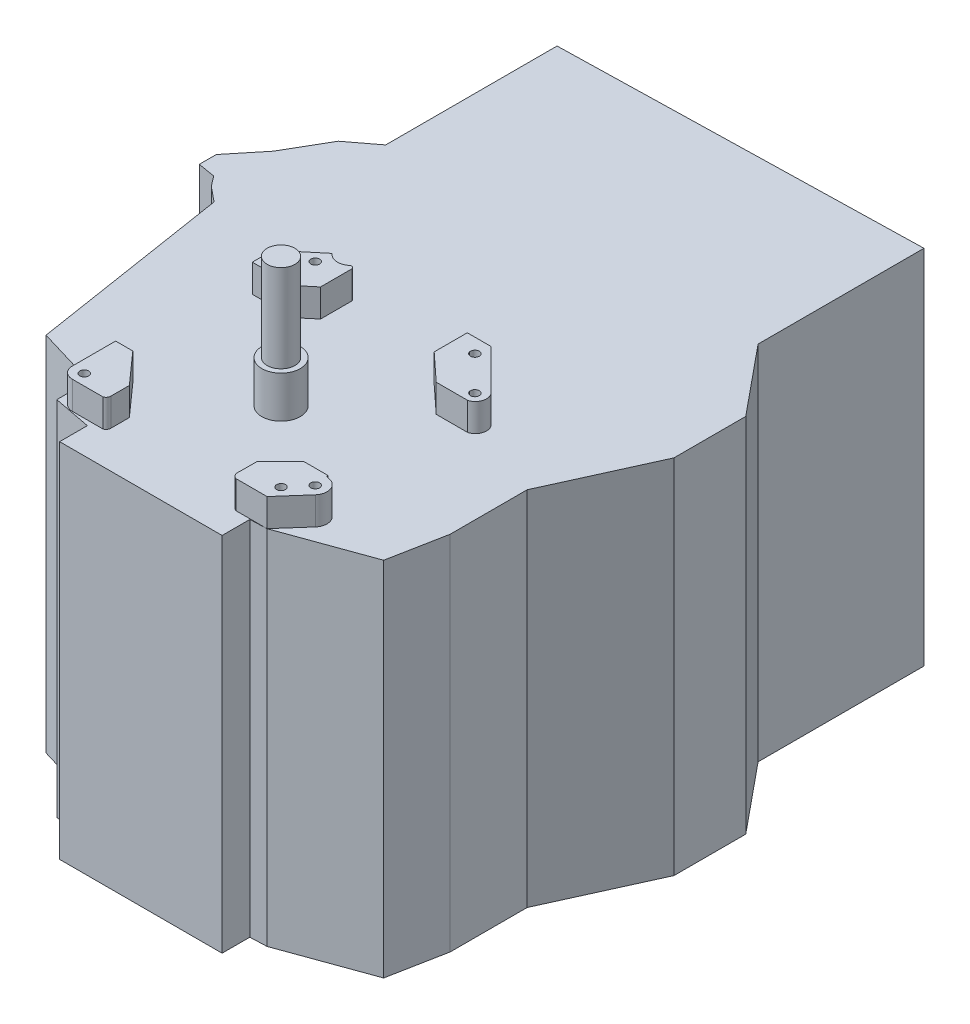
SolidWorks part; units mm, degrees
ref_plane "Front Plane" through (0, 0, 0) normal (0, 0, 1) x (1, 0, 0)
ref_plane "Top Plane" through (0, 0, 0) normal (0, 1, 0) x (1, 0, 0)
ref_plane "Right Plane" through (0, 0, 0) normal (1, 0, 0) x (0, 0, -1)
sketch "Sketch1" plane through (0, 0, 0) normal (0, 1, 0) x (1, 0, 0)
  line L0 (0.0612, 0.1182) -> (-126.9388, 0.1182) construction
  line L1 (-96.8371, 97.1503) -> (-71.6407, 118.188)
  line L2 (-50.3848, 114.8458) -> (-50.3848, 86.3868)
  line L3 (-50.3848, 86.3868) -> (-64.2052, 74.8474)
  line L4 (-64.2052, 74.8474) -> (-101.118, 74.8474)
  line L5 (-101.118, 74.8474) -> (-101.118, 86.3868)
  line L6 (74.669, 117.1527) -> (110.8217, 80.9999)
  line L7 (106.4734, 63.9008) -> (77.6795, 63.9008)
  line L8 (77.6795, 63.9008) -> (52.8172, 86.9128)
  line L9 (52.8172, 86.9128) -> (52.8172, 117.1527)
  line L10 (52.8172, 117.1527) -> (74.669, 117.1527)
  line L11 (101.9355, -59.2136) -> (79.8915, -59.2136)
  line L12 (79.8915, -59.2136) -> (58.6662, -80.129)
  line L13 (58.6662, -80.129) -> (58.5329, -98.2615)
  line L14 (62.5394, -103.6781) -> (90.8914, -103.6781)
  line L15 (90.8914, -103.6781) -> (111.5999, -80.2182)
  line L16 (-101.118, -49.8827) -> (-85.4463, -49.8827)
  line L17 (-85.4463, -49.8827) -> (-59.7593, -78.7019)
  line L18 (-59.7593, -78.7019) -> (-59.7593, -95.602)
  line L19 (-62.6519, -99.786) -> (-90.7515, -99.786)
  line L20 (-101.118, -90.5363) -> (-101.118, -49.8827)
  arc A0 (-71.6407, 118.188) -> (-54.1704, 116.6166) centre (-62.1198, 126.1375) ccw
  arc A1 (-54.1704, 116.6166) -> (-50.3848, 114.8458) centre (-52.6918, 114.8458) cw
  arc A2 (-101.118, 86.3868) -> (-96.8371, 97.1503) centre (-85.4463, 86.3868) cw
  arc A3 (110.8217, 80.9999) -> (106.4734, 63.9008) centre (103.5647, 73.7429) cw
  arc A4 (58.5329, -98.2615) -> (62.5394, -103.6781) centre (64.1419, -98.3027) ccw
  arc A5 (111.5999, -80.2182) -> (103.7376, -61.066) centre (102.9472, -72.5803) ccw
  arc A6 (103.7376, -61.066) -> (101.9355, -59.2136) centre (103.8701, -59.1342) cw
  arc A7 (-59.7593, -95.602) -> (-62.6519, -99.786) centre (-64.2316, -95.602) cw
  arc A8 (-90.7515, -99.786) -> (-101.118, -90.5363) centre (-90.7515, -89.3521) cw
  circle A9 centre (0, 0) radius 126.9678 construction
  dimension "D1" = 127
extrude "Boss-Extrude1" add sketch "Sketch1" along normal blind 25.4
sketch "Sketch2" plane through (0, 0, 0) normal (0, -1, 0) x (1, 0, 0)
  line L1 (-240.03, 129.54) -> (240.03, 129.54)
  line L2 (-240.03, 129.54) -> (-240.03, -429.26)
  line L3 (-240.03, -429.26) -> (240.03, -429.26)
  line L4 (240.03, 129.54) -> (240.03, -429.26)
  line L5 (-240.03, 129.54) -> (240.03, -429.26) construction
  line L6 (-240.03, -429.26) -> (240.03, 129.54) construction
  point P0 (0, -149.86)
  point P5 (0, 0)
  point P6 (0, 129.54)
  point P8 (-39.6101, -204.7195)
  dimension "D1" = 480.06
  dimension "D2" = 558.8
  dimension "D3" = 129.54
extrude "Boss-Extrude2" add sketch "Sketch2" along normal blind 330.2
sketch "Sketch3" plane through (0, 25.4, 0) normal (0, 1, 0) x (1, 0, 0)
  line L0 (-73.1456, 105.4562) -> (107.3629, -73.241) construction
  line L1 (0, -127) -> (0, 127) construction
  line L2 (127, 0) -> (-127, 0) construction
  line L3 (0, 0) -> (72.8442, 104.0323) construction
  line L4 (104.0323, 72.8442) -> (0, 0) construction
  line L5 (104.0323, -72.8442) -> (0, 0) construction
  line L6 (89.8026, -89.8026) -> (0, 0) construction
  line L7 (-89.8026, -89.8026) -> (0, 0) construction
  line L8 (-89.8026, 89.8026) -> (0, 0) construction
  line L9 (0, 0) -> (-72.8442, 104.0323) construction
  circle A0 centre (0, 0) radius 127 construction
  circle A1 centre (-72.8442, 104.0323) radius 4
  circle A2 centre (-89.8026, 89.8026) radius 4
  circle A3 centre (72.8442, 104.0323) radius 4
  circle A4 centre (104.0323, 72.8442) radius 4
  circle A5 centre (104.0323, -72.8442) radius 4
  circle A6 centre (89.8026, -89.8026) radius 4
  circle A7 centre (-89.8026, -89.8026) radius 4
  dimension "D1" = 254
  dimension "D10" = 8
  dimension "D2" = 254
  dimension "D3" = 45
  dimension "D4" = 35
  dimension "D5" = 35
  dimension "D6" = 35
  dimension "D7" = 35
  dimension "D8" = 45
  dimension "D9" = 45
extrude "Cut-Extrude1" cut sketch "Sketch3" against normal blind 25.4
sketch "Sketch4" plane through (0, 0, 0) normal (0, 1, 0) x (1, 0, 0)
  line L0 (-158.2793, 410.1601) -> (-158.2793, 253.7577)
  line L1 (-158.2793, 253.7577) -> (-182.8856, 235.0917)
  line L2 (-182.8856, 235.0917) -> (-204.6295, 197.5341)
  line L3 (-204.6295, 197.5341) -> (-228.0206, 168.8718)
  line L4 (-228.0206, 168.8718) -> (-228.0206, 153.3875)
  line L5 (-228.0206, 153.3875) -> (-212.2069, 150.7519)
  line L6 (-212.2069, 150.7519) -> (-205.2435, 141.5726)
  line L7 (-205.2435, 141.5726) -> (-191.5444, 130.3928)
  line L8 (-191.5444, 130.3928) -> (-162.9288, -51.578)
  line L9 (-162.9288, -51.578) -> (-107.0613, -68.3146)
  line L10 (-107.0613, -68.3146) -> (-107.0613, -97.6129)
  line L11 (-107.0613, -97.6129) -> (-72.5447, -104.2414)
  line L12 (-72.5447, -104.2414) -> (-72.5447, -129.54)
  line L13 (240.03, -129.54) -> (-240.03, -129.54) construction
  line L14 (-72.5447, -129.54) -> (75.7243, -129.54)
  line L15 (75.7243, -129.54) -> (75.7243, -104.2414)
  line L16 (75.7243, -104.2414) -> (90.8914, -103.6781)
  line L17 (90.8914, -103.6781) -> (169.0362, -75.4)
  line L18 (169.0362, -75.4) -> (178.8182, -24.4619)
  line L19 (178.8182, -24.4619) -> (178.8182, 45.8045)
  line L20 (178.8182, 45.8045) -> (220.5766, 137.9854)
  line L21 (220.5766, 137.9854) -> (220.5766, 203.5231)
  line L22 (220.5766, 203.5231) -> (169.0362, 266.3134)
  line L23 (169.0362, 266.3134) -> (169.0362, 417.7177)
  line L24 (169.0362, 417.7177) -> (-158.2793, 410.1601)
  circle A0 centre (0, 0) radius 127 construction
extrude "Cut-Extrude2" cut sketch "Sketch4" against normal through all flip side to cut
sketch "Sketch5" plane through (0, 0, 0) normal (1, 0, 0) x (0, 0, -1)
  line L0 (-17.5, 0) -> (-17.5, 38)
  line L1 (-24.4619, 0) -> (45.8045, 0) construction
  line L2 (-17.5, 38) -> (-12.695, 38)
  line L3 (-12.695, 38) -> (-12.695, 118)
  line L4 (-12.695, 118) -> (0, 118)
  line L5 (0, 118) -> (0, 0)
  dimension "D1" = 17.5
  dimension "D2" = 12.695
  dimension "D3" = 38
  dimension "D4" = 80
revolve "Revolve-Thin1" add sketch "Sketch5" angle 360 about L5
